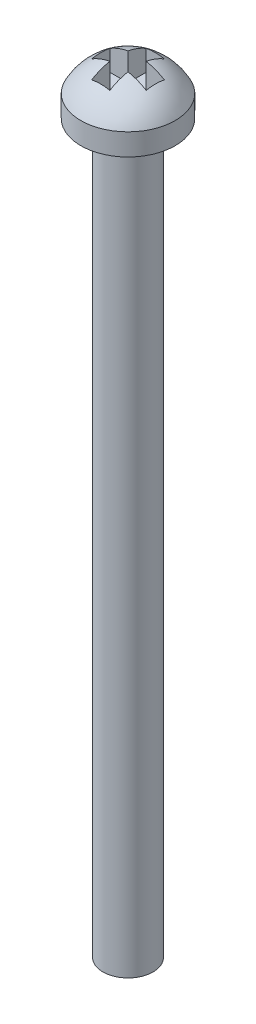
SolidWorks part; units mm, degrees
ref_plane "Front Plane" through (0, 0, 0) normal (0, 0, 1) x (1, 0, 0)
ref_plane "Top Plane" through (0, 0, 0) normal (0, 1, 0) x (1, 0, 0)
ref_plane "Right Plane" through (0, 0, 0) normal (1, 0, 0) x (0, 0, -1)
sketch "Sketch1" plane through (0, 0, 0) normal (0, 0, 1) x (1, 0, 0)
  line L0 (0, 0) -> (0, 50.8)
  line L1 (0, 50.8) -> (1.7526, 50.8)
  line L2 (1.7526, 50.8) -> (1.7526, 0)
  line L3 (1.7526, 0) -> (0, 0)
  line L4 (0, 50.8) -> (3.302, 50.8)
  line L5 (3.302, 50.8) -> (3.302, 52.324)
  line L6 (0, -8.9323) -> (0, 64.7263) construction
  line L7 (0, 50.6772) -> (0, 50.8)
  line L8 (0, 50.6772) -> (0, 54.3671)
  arc A0 (3.302, 52.324) -> (0, 54.3671) centre (0, 50.6772) ccw
  dimension "D1" = 50.8
  dimension "D2" = 1.7526
  dimension "D3" = 1.524
  dimension "D4" = 3.302
revolve "Revolve1" add sketch "Sketch1" angle 360 about L6
ref_plane "Plane1" through (0, 52.324, 0) normal (0, -1, 0) x (-1, 0, 0)
sketch "Sketch2" plane through (0, 52.324, 0) normal (0, -1, 0) x (-1, 0, 0)
  line L0 (0.635, 0.635) -> (1.905, 0.635)
  line L1 (-1.905, -0.635) -> (-0.635, -0.635)
  line L2 (-1.905, -0.635) -> (-1.905, 0.635)
  line L3 (-1.905, 0.635) -> (-0.635, 0.635)
  line L4 (1.905, -0.635) -> (1.905, 0.635)
  line L5 (-1.905, 0) -> (0, 0) construction
  line L6 (-0.9525, 0.4762) -> (0, 0) construction
  line L7 (-0.635, -1.905) -> (0.635, -1.905)
  line L8 (-0.635, -1.905) -> (-0.635, -0.635)
  line L9 (-0.635, 1.905) -> (0.635, 1.905)
  line L10 (0.635, -1.905) -> (0.635, -0.635)
  line L11 (-0.4763, -0.9525) -> (0, 0) construction
  line L12 (-0.3753, 1.1258) -> (0, 0) construction
  line L13 (-0.635, 0.635) -> (-0.635, 1.905)
  line L14 (0, 0) -> (0.9525, 0.4763) construction
  line L15 (0.635, -0.635) -> (1.905, -0.635)
  line L16 (0.2982, -0.8947) -> (0.635, -1.905) construction
  line L17 (0, 0) -> (1.905, 0) construction
  line L18 (0.635, 0.635) -> (0.635, 1.905)
  line L19 (0, 1.905) -> (0, 0) construction
  line L20 (0, 0) -> (0, -1.905) construction
  point P0 (0, 0)
  point P6 (0, 0)
  dimension "D1" = 3.81
  dimension "D2" = 3.81
  dimension "D3" = 1.27
  dimension "D4" = 1.27
extrude "Cut-Extrude1" cut sketch "Sketch2" against normal up to next
